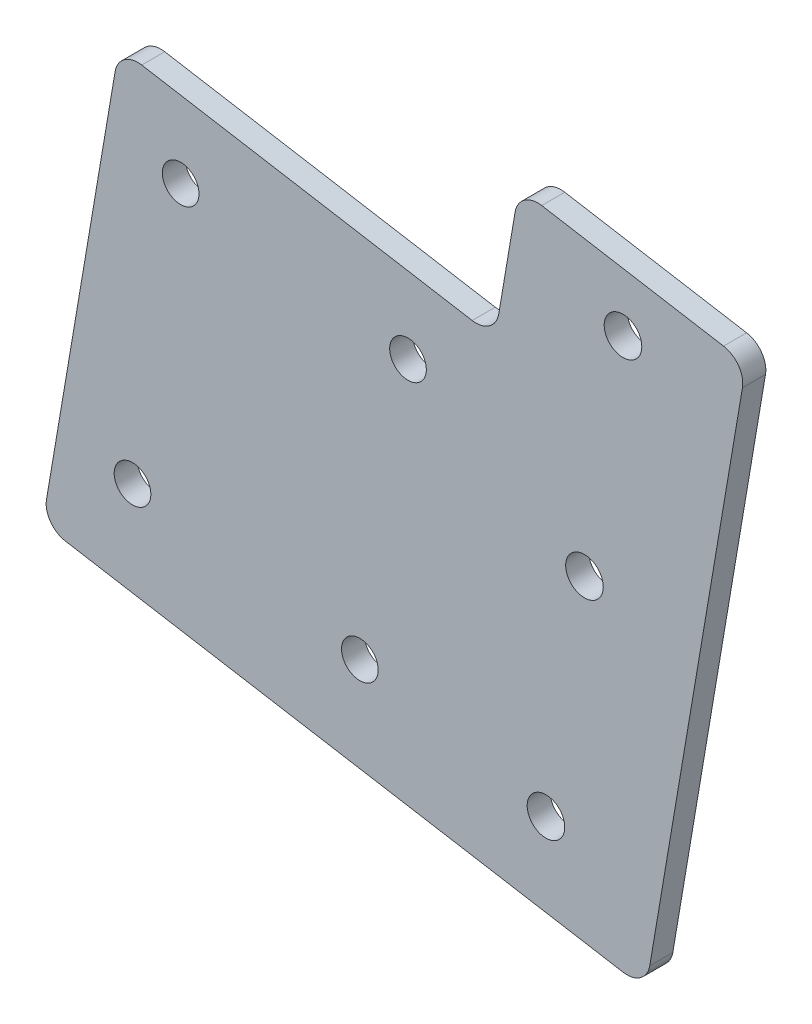
SolidWorks part; units mm, degrees
ref_plane "Front" through (0, 0, 0) normal (0, 0, 1) x (1, 0, 0)
ref_plane "Top" through (0, 0, 0) normal (0, 1, 0) x (1, 0, 0)
ref_plane "Right" through (0, 0, 0) normal (1, 0, 0) x (0, 0, -1)
sketch "Sketch1" plane through (0, 0, 0) normal (0, 0, 1) x (1, 0, 0)
  line L0 (-12.9599, -36.9844) -> (28.4499, -44.0009)
  line L1 (45.0856, -97.862) -> (56.1437, -32.5999)
  line L2 (45.0856, -97.862) -> (-21.3672, -86.6022)
  line L3 (-21.3672, -86.6022) -> (-12.9599, -36.9844)
  line L4 (56.1437, -32.5999) -> (31.1006, -28.3566)
  line L6 (-13.4611, -39.9422) -> (-15.0523, -49.3334) construction
  line L8 (20.0426, -93.6187) -> (-21.3672, -86.6022) construction
  line L10 (69.9345, 48.79) -> (36.599, -147.9481) construction
  line L16 (28.4499, -44.0009) -> (31.1006, -28.3566)
  line L18 (35.9804, 0.4429) -> (32.5858, -19.5915) construction
  line L20 (20.5623, -42.6644) -> (-11.974, -37.1514) construction
  circle A0 centre (-6.1631, -46.5543) radius 2.0193
  circle A1 centre (-11.4673, -77.8581) radius 2.0193
  circle A2 centre (18.8799, -50.7977) radius 2.0193
  circle A3 centre (13.5758, -82.1015) radius 2.0193
  circle A4 centre (38.318, -61.7821) radius 2.0701
  circle A5 centre (34.0747, -86.8251) radius 2.0701
  circle A6 centre (42.5613, -36.739) radius 2.0701
  arc A7 (42.8318, -34.6867) -> (42.1406, -38.7659) centre (42.5613, -36.739) ccw construction
  arc A9 (38.5885, -59.7297) -> (37.8973, -63.809) centre (38.318, -61.7821) ccw construction
  arc A10 (34.3452, -84.7727) -> (33.654, -88.852) centre (34.0747, -86.8251) ccw construction
  circle A11 centre (13.5758, -82.1015) radius 2.0193 construction
  circle A12 centre (18.8799, -50.7977) radius 2.0193 construction
  circle A13 centre (-6.1631, -46.5543) radius 2.0193 construction
  circle A14 centre (-11.4673, -77.8581) radius 2.0193 construction
  point P0 (0, 0)
  dimension "D2" = 6.35
extrude "Boss-Extrude1" add sketch "Sketch1" along normal blind 2.54
fillet "Fillet2" radius 2.54 6 edges at (28.4499, -44.0009, 1.27) (31.1006, -28.3566, 1.27) (56.1437, -32.5999, 1.27) (45.0856, -97.862, 1.27) (-21.3672, -86.6022, 1.27) (-12.9599, -36.9844, 1.27)
